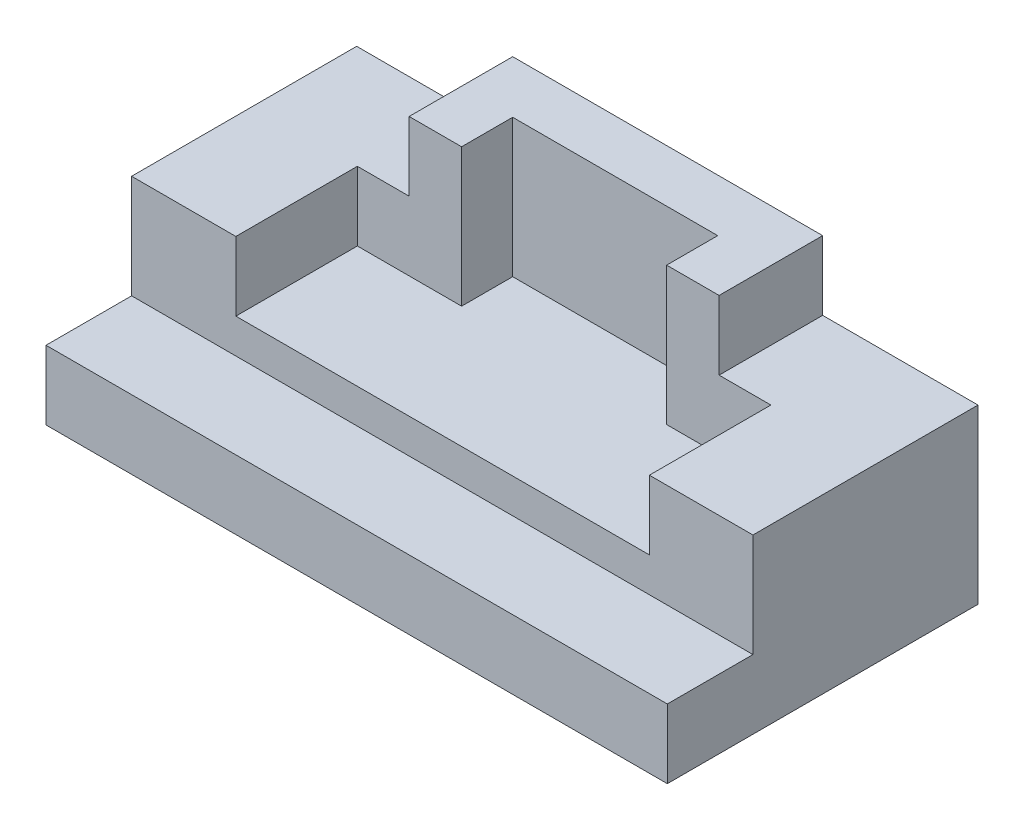
SolidWorks part; units mm, degrees
ref_plane "Front Plane" through (0, 0, 0) normal (0, 0, 1) x (1, 0, 0)
ref_plane "Top Plane" through (0, 0, 0) normal (0, 1, 0) x (1, 0, 0)
ref_plane "Right Plane" through (0, 0, 0) normal (1, 0, 0) x (0, 0, -1)
sketch "Sketch1" plane through (0, 0, 0) normal (1, 0, 0) x (0, 0, -1)
  line L0 (-28.575, 0) -> (28.575, 0)
  line L1 (28.575, 0) -> (28.575, 31.75)
  line L4 (-12.827, 31.75) -> (-12.827, 12.7)
  line L5 (-12.827, 12.7) -> (-28.575, 12.7)
  line L6 (-28.575, 12.7) -> (-28.575, 0)
  line L7 (28.575, 31.75) -> (-12.827, 31.75)
  point P4 (0, 0)
  dimension "D1" = 57.15
  dimension "D2" = 31.75
  dimension "D3" = 41.402
  dimension "D4" = 12.7
extrude "Boss-Extrude1" add sketch "Sketch1" along normal mid plane 114.3
sketch "Sketch2" plane through (0, 31.75, 0) normal (0, 1, 0) x (1, 0, 0)
  line L0 (-28.448, 28.575) -> (28.575, 28.575)
  line L1 (57.15, 28.575) -> (-57.15, 28.575) construction
  line L2 (28.575, 28.575) -> (28.575, 9.525)
  line L3 (28.575, 9.525) -> (18.923, 9.525)
  line L4 (18.923, 9.525) -> (18.923, 18.923)
  line L5 (18.923, 18.923) -> (-18.796, 18.923)
  line L6 (-18.796, 18.923) -> (-18.796, 9.525)
  line L7 (-18.796, 9.525) -> (-28.448, 9.525)
  line L8 (-28.448, 9.525) -> (-28.448, 28.575)
  dimension "D1" = 28.702
  dimension "D2" = 28.575
  dimension "D3" = 9.652
  dimension "D4" = 19.05
  dimension "D5" = 9.652
extrude "Boss-Extrude2" add sketch "Sketch2" along normal blind 12.7
sketch "Sketch3" plane through (0, 44.45, 0) normal (0, 1, 0) x (1, 0, 0)
  line L0 (-18.796, 9.525) -> (-18.796, 18.923)
  line L1 (-18.796, 18.923) -> (18.923, 18.923)
  line L2 (18.923, 18.923) -> (18.923, 9.525)
  line L3 (18.923, 9.525) -> (38.1, 9.525)
  line L4 (38.1, 9.525) -> (38.1, -12.827)
  line L5 (57.15, -12.827) -> (-57.15, -12.827) construction
  line L6 (38.1, -12.827) -> (-37.973, -12.827)
  line L7 (57.15, -12.827) -> (-57.15, -12.827) construction
  line L8 (-37.973, -12.827) -> (-37.973, 9.525)
  line L9 (-37.973, 9.525) -> (-18.796, 9.525)
  line L10 (57.15, 28.575) -> (57.15, -12.827) construction
  dimension "D1" = 19.05
extrude "Cut-Extrude1" cut sketch "Sketch3" against normal blind 25.4
